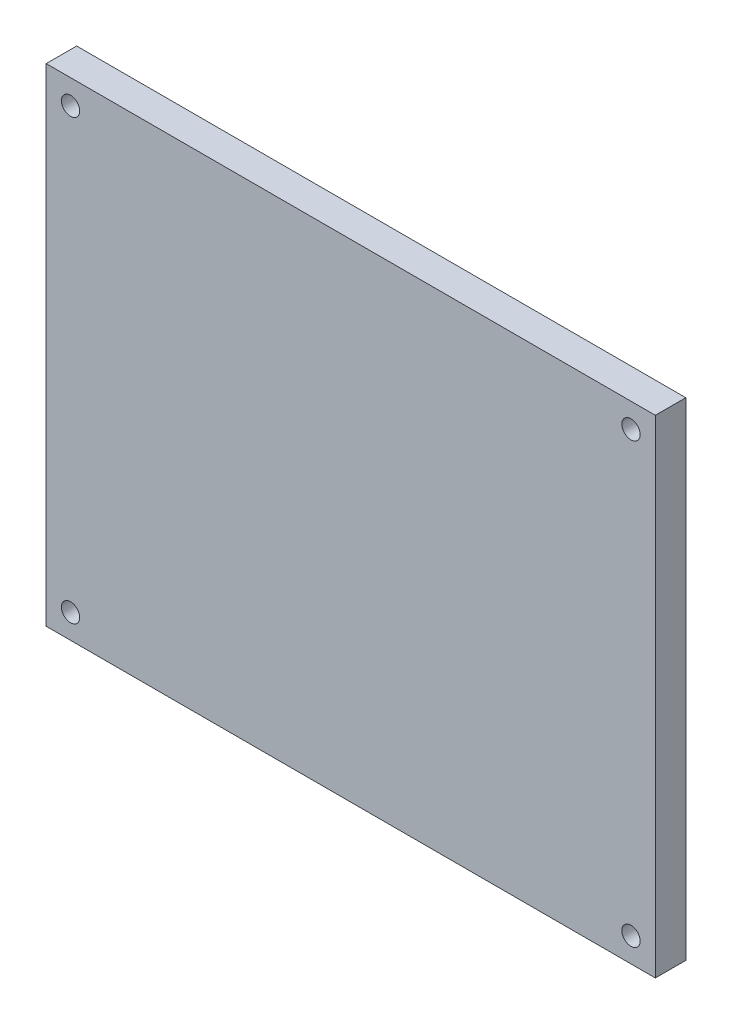
SolidWorks part; units mm, degrees
ref_plane "Plan de face" through (0, 0, 0) normal (0, 0, 1) x (1, 0, 0)
ref_plane "Plan de dessus" through (0, 0, 0) normal (0, 1, 0) x (1, 0, 0)
ref_plane "Plan de droite" through (0, 0, 0) normal (1, 0, 0) x (0, 0, -1)
sketch "Esquisse1" plane through (0, 0, 0) normal (0, 0, 1) x (1, 0, 0)
  line L0 (-46, 36) -> (46, 36) construction
  line L1 (50, -40) -> (-50, -40)
  line L2 (50, -40) -> (50, 40)
  line L3 (50, 40) -> (-50, 40)
  line L4 (-50, -40) -> (-50, 40)
  line L5 (50, -40) -> (-50, 40) construction
  line L6 (50, 40) -> (-50, -40) construction
  line L7 (-46, 36) -> (-46, -36) construction
  circle A0 centre (-46, 36) radius 1.5
  circle A1 centre (46, 36) radius 1.5
  circle A2 centre (46, -36) radius 1.5
  circle A3 centre (-46, -36) radius 1.5
  point P0 (0, 0)
  dimension "D3" = 3
  dimension "D1" = 80
  dimension "D2" = 100
  dimension "D4" = 4
  dimension "D5" = 4
  dimension "D8" = 92
  dimension "D9" = 72
  dimension "D10" = 92
  dimension "D6" = 2
  dimension "D7" = 2
extrude "Boss.-Extru.1" add sketch "Esquisse1" along normal blind 5
